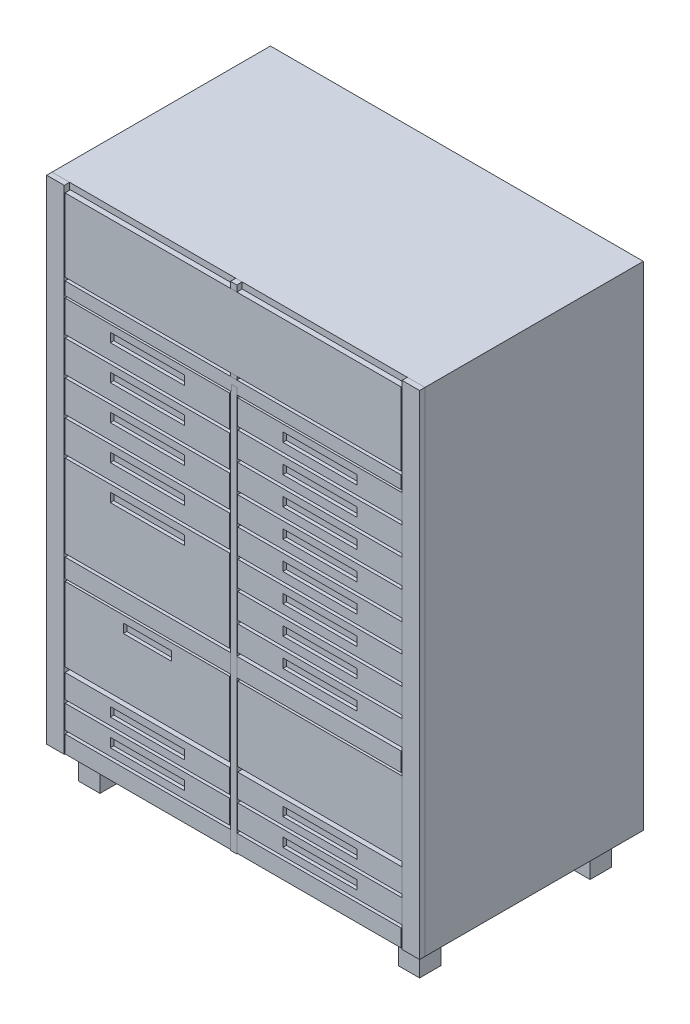
SolidWorks part; units mm, degrees
ref_plane "Front Plane" through (0, 0, 0) normal (0, 0, 1) x (1, 0, 0)
ref_plane "Top Plane" through (0, 0, 0) normal (0, 1, 0) x (1, 0, 0)
ref_plane "Right Plane" through (0, 0, 0) normal (1, 0, 0) x (0, 0, -1)
other "Configuration Table"
sketch "Sketch1" plane through (0, 0, 0) normal (0, 0, 1) x (1, 0, 0)
  line L1 (0, 120) -> (1400, 120)
  line L2 (0, 120) -> (0, 1970)
  line L3 (0, 1970) -> (1400, 1970)
  line L4 (1400, 120) -> (1400, 1970)
extrude "govde_kasa" add sketch "Sketch1" against normal blind 820 separate body
sketch "Sketch2" plane through (0, 0, 0) normal (0, 1, 0) x (1, 0, 0)
  line L1 (60, 40) -> (140, 40)
  line L2 (60, 40) -> (60, 120)
  line L3 (60, 120) -> (140, 120)
  line L4 (140, 40) -> (140, 120)
extrude "ayak_1" add sketch "Sketch2" along normal blind 120 separate body
sketch "Sketch3" plane through (0, 0, 0) normal (0, 1, 0) x (1, 0, 0)
  line L1 (1260, 40) -> (1340, 40)
  line L2 (1260, 40) -> (1260, 120)
  line L3 (1260, 120) -> (1340, 120)
  line L4 (1340, 40) -> (1340, 120)
extrude "ayak_2" add sketch "Sketch3" along normal blind 120 separate body
sketch "Sketch4" plane through (0, 0, 0) normal (0, 1, 0) x (1, 0, 0)
  line L1 (60, 680) -> (140, 680)
  line L2 (60, 680) -> (60, 760)
  line L3 (60, 760) -> (140, 760)
  line L4 (140, 680) -> (140, 760)
extrude "ayak_3" add sketch "Sketch4" along normal blind 120 separate body
sketch "Sketch5" plane through (0, 0, 0) normal (0, 1, 0) x (1, 0, 0)
  line L1 (1260, 680) -> (1340, 680)
  line L2 (1260, 680) -> (1260, 760)
  line L3 (1260, 760) -> (1340, 760)
  line L4 (1340, 680) -> (1340, 760)
extrude "ayak_4" add sketch "Sketch5" along normal blind 120 separate body
sketch "Sketch6" plane through (0, 0, 0) normal (0, 0, 1) x (1, 0, 0)
  line L1 (0, 120) -> (66, 120)
  line L2 (0, 120) -> (0, 1970)
  line L3 (0, 1970) -> (66, 1970)
  line L4 (66, 120) -> (66, 1970)
extrude "sove_sol" add sketch "Sketch6" along normal blind 20 separate body
sketch "Sketch7" plane through (0, 0, 0) normal (0, 0, 1) x (1, 0, 0)
  line L1 (690, 120) -> (714, 120)
  line L2 (690, 120) -> (690, 1970)
  line L3 (690, 1970) -> (714, 1970)
  line L4 (714, 120) -> (714, 1970)
extrude "sove_orta" add sketch "Sketch7" along normal blind 20 separate body
sketch "Sketch8" plane through (0, 0, 0) normal (0, 0, 1) x (1, 0, 0)
  line L1 (1334, 120) -> (1400, 120)
  line L2 (1334, 120) -> (1334, 1970)
  line L3 (1334, 1970) -> (1400, 1970)
  line L4 (1400, 120) -> (1400, 1970)
extrude "sove_sag" add sketch "Sketch8" along normal blind 20 separate body
sketch "Sketch9" plane through (0, 0, 0) normal (0, 0, 1) x (1, 0, 0)
  line L1 (69, 1673) -> (1331, 1673)
  line L2 (69, 1673) -> (69, 1947)
  line L3 (69, 1947) -> (1331, 1947)
  line L4 (1331, 1673) -> (1331, 1947)
extrude "panel_sogutma" add sketch "Sketch9" along normal blind 20 separate body
sketch "Sketch10" plane through (0, 0, 0) normal (0, 0, 1) x (1, 0, 0)
  line L1 (69, 1613) -> (1331, 1613)
  line L2 (69, 1613) -> (69, 1661)
  line L3 (69, 1661) -> (1331, 1661)
  line L4 (1331, 1613) -> (1331, 1661)
extrude "panel_bant_ust" add sketch "Sketch10" along normal blind 20 separate body
sketch "Sketch11" plane through (0, 0, 0) normal (0, 0, 1) x (1, 0, 0)
  line L1 (69, 1487) -> (687, 1487)
  line L2 (69, 1487) -> (69, 1605)
  line L3 (69, 1605) -> (687, 1605)
  line L4 (687, 1487) -> (687, 1605)
extrude "cekmece_icecek_1" add sketch "Sketch11" along normal blind 20 separate body
sketch "Sketch12" plane through (0, 0, 0) normal (0, 0, 1) x (1, 0, 0)
  line L1 (238.95, 1545) -> (517.05, 1545)
  line L2 (238.95, 1545) -> (238.95, 1579)
  line L3 (238.95, 1579) -> (517.05, 1579)
  line L4 (517.05, 1545) -> (517.05, 1579)
extrude "cekmece_icecek_1_kulp" cut sketch "Sketch12" along normal blind 13 from offset 7
sketch "Sketch13" plane through (0, 0, 0) normal (0, 0, 1) x (1, 0, 0)
  line L1 (69, 1357) -> (687, 1357)
  line L2 (69, 1357) -> (69, 1475)
  line L3 (69, 1475) -> (687, 1475)
  line L4 (687, 1357) -> (687, 1475)
extrude "cekmece_icecek_2" add sketch "Sketch13" along normal blind 20 separate body
sketch "Sketch14" plane through (0, 0, 0) normal (0, 0, 1) x (1, 0, 0)
  line L1 (238.95, 1415) -> (517.05, 1415)
  line L2 (238.95, 1415) -> (238.95, 1449)
  line L3 (238.95, 1449) -> (517.05, 1449)
  line L4 (517.05, 1415) -> (517.05, 1449)
extrude "cekmece_icecek_2_kulp" cut sketch "Sketch14" along normal blind 13 from offset 7
sketch "Sketch15" plane through (0, 0, 0) normal (0, 0, 1) x (1, 0, 0)
  line L1 (69, 1227) -> (687, 1227)
  line L2 (69, 1227) -> (69, 1345)
  line L3 (69, 1345) -> (687, 1345)
  line L4 (687, 1227) -> (687, 1345)
extrude "cekmece_icecek_3" add sketch "Sketch15" along normal blind 20 separate body
sketch "Sketch16" plane through (0, 0, 0) normal (0, 0, 1) x (1, 0, 0)
  line L1 (238.95, 1285) -> (517.05, 1285)
  line L2 (238.95, 1285) -> (238.95, 1319)
  line L3 (238.95, 1319) -> (517.05, 1319)
  line L4 (517.05, 1285) -> (517.05, 1319)
extrude "cekmece_icecek_3_kulp" cut sketch "Sketch16" along normal blind 13 from offset 7
sketch "Sketch17" plane through (0, 0, 0) normal (0, 0, 1) x (1, 0, 0)
  line L1 (69, 1097) -> (687, 1097)
  line L2 (69, 1097) -> (69, 1215)
  line L3 (69, 1215) -> (687, 1215)
  line L4 (687, 1097) -> (687, 1215)
extrude "cekmece_icecek_4" add sketch "Sketch17" along normal blind 20 separate body
sketch "Sketch18" plane through (0, 0, 0) normal (0, 0, 1) x (1, 0, 0)
  line L1 (238.95, 1155) -> (517.05, 1155)
  line L2 (238.95, 1155) -> (238.95, 1189)
  line L3 (238.95, 1189) -> (517.05, 1189)
  line L4 (517.05, 1155) -> (517.05, 1189)
extrude "cekmece_icecek_4_kulp" cut sketch "Sketch18" along normal blind 13 from offset 7
sketch "Sketch19" plane through (0, 0, 0) normal (0, 0, 1) x (1, 0, 0)
  line L1 (69, 775) -> (687, 775)
  line L2 (69, 775) -> (69, 1085)
  line L3 (69, 1085) -> (687, 1085)
  line L4 (687, 775) -> (687, 1085)
extrude "cekmece_1L" add sketch "Sketch19" along normal blind 20 separate body
sketch "Sketch20" plane through (0, 0, 0) normal (0, 0, 1) x (1, 0, 0)
  line L1 (238.95, 1025) -> (517.05, 1025)
  line L2 (238.95, 1025) -> (238.95, 1059)
  line L3 (238.95, 1059) -> (517.05, 1059)
  line L4 (517.05, 1025) -> (517.05, 1059)
extrude "cekmece_1L_kulp" cut sketch "Sketch20" along normal blind 13 from offset 7
sketch "Sketch21" plane through (0, 0, 0) normal (0, 0, 1) x (1, 0, 0)
  line L1 (717, 1512) -> (1335, 1512)
  line L2 (717, 1512) -> (717, 1605)
  line L3 (717, 1605) -> (1335, 1605)
  line L4 (1335, 1512) -> (1335, 1605)
extrude "cekmece_taze_1" add sketch "Sketch21" along normal blind 20 separate body
sketch "Sketch22" plane through (0, 0, 0) normal (0, 0, 1) x (1, 0, 0)
  line L1 (886.95, 1545) -> (1165.05, 1545)
  line L2 (886.95, 1545) -> (886.95, 1579)
  line L3 (886.95, 1579) -> (1165.05, 1579)
  line L4 (1165.05, 1545) -> (1165.05, 1579)
extrude "cekmece_taze_1_kulp" cut sketch "Sketch22" along normal blind 13 from offset 7
sketch "Sketch23" plane through (0, 0, 0) normal (0, 0, 1) x (1, 0, 0)
  line L1 (717, 1407) -> (1335, 1407)
  line L2 (717, 1407) -> (717, 1500)
  line L3 (717, 1500) -> (1335, 1500)
  line L4 (1335, 1407) -> (1335, 1500)
extrude "cekmece_taze_2" add sketch "Sketch23" along normal blind 20 separate body
sketch "Sketch24" plane through (0, 0, 0) normal (0, 0, 1) x (1, 0, 0)
  line L1 (886.95, 1440) -> (1165.05, 1440)
  line L2 (886.95, 1440) -> (886.95, 1474)
  line L3 (886.95, 1474) -> (1165.05, 1474)
  line L4 (1165.05, 1440) -> (1165.05, 1474)
extrude "cekmece_taze_2_kulp" cut sketch "Sketch24" along normal blind 13 from offset 7
sketch "Sketch25" plane through (0, 0, 0) normal (0, 0, 1) x (1, 0, 0)
  line L1 (717, 1302) -> (1335, 1302)
  line L2 (717, 1302) -> (717, 1395)
  line L3 (717, 1395) -> (1335, 1395)
  line L4 (1335, 1302) -> (1335, 1395)
extrude "cekmece_taze_3" add sketch "Sketch25" along normal blind 20 separate body
sketch "Sketch26" plane through (0, 0, 0) normal (0, 0, 1) x (1, 0, 0)
  line L1 (886.95, 1335) -> (1165.05, 1335)
  line L2 (886.95, 1335) -> (886.95, 1369)
  line L3 (886.95, 1369) -> (1165.05, 1369)
  line L4 (1165.05, 1335) -> (1165.05, 1369)
extrude "cekmece_taze_3_kulp" cut sketch "Sketch26" along normal blind 13 from offset 7
sketch "Sketch27" plane through (0, 0, 0) normal (0, 0, 1) x (1, 0, 0)
  line L1 (717, 1197) -> (1335, 1197)
  line L2 (717, 1197) -> (717, 1290)
  line L3 (717, 1290) -> (1335, 1290)
  line L4 (1335, 1197) -> (1335, 1290)
extrude "cekmece_taze_4" add sketch "Sketch27" along normal blind 20 separate body
sketch "Sketch28" plane through (0, 0, 0) normal (0, 0, 1) x (1, 0, 0)
  line L1 (886.95, 1230) -> (1165.05, 1230)
  line L2 (886.95, 1230) -> (886.95, 1264)
  line L3 (886.95, 1264) -> (1165.05, 1264)
  line L4 (1165.05, 1230) -> (1165.05, 1264)
extrude "cekmece_taze_4_kulp" cut sketch "Sketch28" along normal blind 13 from offset 7
sketch "Sketch29" plane through (0, 0, 0) normal (0, 0, 1) x (1, 0, 0)
  line L1 (717, 1092) -> (1335, 1092)
  line L2 (717, 1092) -> (717, 1185)
  line L3 (717, 1185) -> (1335, 1185)
  line L4 (1335, 1092) -> (1335, 1185)
extrude "cekmece_taze_5" add sketch "Sketch29" along normal blind 20 separate body
sketch "Sketch30" plane through (0, 0, 0) normal (0, 0, 1) x (1, 0, 0)
  line L1 (886.95, 1125) -> (1165.05, 1125)
  line L2 (886.95, 1125) -> (886.95, 1159)
  line L3 (886.95, 1159) -> (1165.05, 1159)
  line L4 (1165.05, 1125) -> (1165.05, 1159)
extrude "cekmece_taze_5_kulp" cut sketch "Sketch30" along normal blind 13 from offset 7
sketch "Sketch31" plane through (0, 0, 0) normal (0, 0, 1) x (1, 0, 0)
  line L1 (717, 987) -> (1335, 987)
  line L2 (717, 987) -> (717, 1080)
  line L3 (717, 1080) -> (1335, 1080)
  line L4 (1335, 987) -> (1335, 1080)
extrude "cekmece_taze_6" add sketch "Sketch31" along normal blind 20 separate body
sketch "Sketch32" plane through (0, 0, 0) normal (0, 0, 1) x (1, 0, 0)
  line L1 (886.95, 1020) -> (1165.05, 1020)
  line L2 (886.95, 1020) -> (886.95, 1054)
  line L3 (886.95, 1054) -> (1165.05, 1054)
  line L4 (1165.05, 1020) -> (1165.05, 1054)
extrude "cekmece_taze_6_kulp" cut sketch "Sketch32" along normal blind 13 from offset 7
sketch "Sketch33" plane through (0, 0, 0) normal (0, 0, 1) x (1, 0, 0)
  line L1 (717, 882) -> (1335, 882)
  line L2 (717, 882) -> (717, 975)
  line L3 (717, 975) -> (1335, 975)
  line L4 (1335, 882) -> (1335, 975)
extrude "cekmece_taze_7" add sketch "Sketch33" along normal blind 20 separate body
sketch "Sketch34" plane through (0, 0, 0) normal (0, 0, 1) x (1, 0, 0)
  line L1 (886.95, 915) -> (1165.05, 915)
  line L2 (886.95, 915) -> (886.95, 949)
  line L3 (886.95, 949) -> (1165.05, 949)
  line L4 (1165.05, 915) -> (1165.05, 949)
extrude "cekmece_taze_7_kulp" cut sketch "Sketch34" along normal blind 13 from offset 7
sketch "Sketch35" plane through (0, 0, 0) normal (0, 0, 1) x (1, 0, 0)
  line L1 (717, 777) -> (1335, 777)
  line L2 (717, 777) -> (717, 870)
  line L3 (717, 870) -> (1335, 870)
  line L4 (1335, 777) -> (1335, 870)
extrude "cekmece_taze_8" add sketch "Sketch35" along normal blind 20 separate body
sketch "Sketch36" plane through (0, 0, 0) normal (0, 0, 1) x (1, 0, 0)
  line L1 (886.95, 810) -> (1165.05, 810)
  line L2 (886.95, 810) -> (886.95, 844)
  line L3 (886.95, 844) -> (1165.05, 844)
  line L4 (1165.05, 810) -> (1165.05, 844)
extrude "cekmece_taze_8_kulp" cut sketch "Sketch36" along normal blind 13 from offset 7
sketch "Sketch37" plane through (0, 0, 0) normal (0, 0, 1) x (1, 0, 0)
  line L1 (69, 693) -> (1331, 693)
  line L2 (69, 693) -> (69, 763)
  line L3 (69, 763) -> (1331, 763)
  line L4 (1331, 693) -> (1331, 763)
extrude "panel_ayirici_PU80" add sketch "Sketch37" along normal blind 20 separate body
sketch "Sketch38" plane through (0, 0, 0) normal (0, 0, 1) x (1, 0, 0)
  line L1 (69, 406) -> (687, 406)
  line L2 (69, 406) -> (69, 684)
  line L3 (69, 684) -> (687, 684)
  line L4 (687, 406) -> (687, 684)
extrude "klape_kaset_kati" add sketch "Sketch38" along normal blind 20 separate body
sketch "Sketch39" plane through (0, 0, 0) normal (0, 0, 1) x (1, 0, 0)
  line L1 (288, 624) -> (468, 624)
  line L2 (288, 624) -> (288, 658)
  line L3 (288, 658) -> (468, 658)
  line L4 (468, 624) -> (468, 658)
extrude "klape_kaset_kati_kulp" cut sketch "Sketch39" along normal blind 13 from offset 7
sketch "Sketch40" plane through (0, 0, 0) normal (0, 0, 1) x (1, 0, 0)
  line L1 (717, 406) -> (1335, 406)
  line L2 (717, 406) -> (717, 684)
  line L3 (717, 684) -> (1335, 684)
  line L4 (1335, 406) -> (1335, 684)
extrude "panel_bos_bant" add sketch "Sketch40" along normal blind 20 separate body
sketch "Sketch41" plane through (0, 0, 0) normal (0, 0, 1) x (1, 0, 0)
  line L1 (69, 300) -> (687, 300)
  line L2 (69, 300) -> (69, 388)
  line L3 (69, 388) -> (687, 388)
  line L4 (687, 300) -> (687, 388)
extrude "cekmece_donmus_1" add sketch "Sketch41" along normal blind 20 separate body
sketch "Sketch42" plane through (0, 0, 0) normal (0, 0, 1) x (1, 0, 0)
  line L1 (238.95, 328) -> (517.05, 328)
  line L2 (238.95, 328) -> (238.95, 362)
  line L3 (238.95, 362) -> (517.05, 362)
  line L4 (517.05, 328) -> (517.05, 362)
extrude "cekmece_donmus_1_kulp" cut sketch "Sketch42" along normal blind 13 from offset 7
sketch "Sketch43" plane through (0, 0, 0) normal (0, 0, 1) x (1, 0, 0)
  line L1 (69, 200) -> (687, 200)
  line L2 (69, 200) -> (69, 288)
  line L3 (69, 288) -> (687, 288)
  line L4 (687, 200) -> (687, 288)
extrude "cekmece_donmus_2" add sketch "Sketch43" along normal blind 20 separate body
sketch "Sketch44" plane through (0, 0, 0) normal (0, 0, 1) x (1, 0, 0)
  line L1 (238.95, 228) -> (517.05, 228)
  line L2 (238.95, 228) -> (238.95, 262)
  line L3 (238.95, 262) -> (517.05, 262)
  line L4 (517.05, 228) -> (517.05, 262)
extrude "cekmece_donmus_2_kulp" cut sketch "Sketch44" along normal blind 13 from offset 7
sketch "Sketch45" plane through (0, 0, 0) normal (0, 0, 1) x (1, 0, 0)
  line L1 (717, 300) -> (1335, 300)
  line L2 (717, 300) -> (717, 388)
  line L3 (717, 388) -> (1335, 388)
  line L4 (1335, 300) -> (1335, 388)
extrude "cekmece_donmus_3" add sketch "Sketch45" along normal blind 20 separate body
sketch "Sketch46" plane through (0, 0, 0) normal (0, 0, 1) x (1, 0, 0)
  line L1 (886.95, 328) -> (1165.05, 328)
  line L2 (886.95, 328) -> (886.95, 362)
  line L3 (886.95, 362) -> (1165.05, 362)
  line L4 (1165.05, 328) -> (1165.05, 362)
extrude "cekmece_donmus_3_kulp" cut sketch "Sketch46" along normal blind 13 from offset 7
sketch "Sketch47" plane through (0, 0, 0) normal (0, 0, 1) x (1, 0, 0)
  line L1 (717, 200) -> (1335, 200)
  line L2 (717, 200) -> (717, 288)
  line L3 (717, 288) -> (1335, 288)
  line L4 (1335, 200) -> (1335, 288)
extrude "cekmece_donmus_4" add sketch "Sketch47" along normal blind 20 separate body
sketch "Sketch48" plane through (0, 0, 0) normal (0, 0, 1) x (1, 0, 0)
  line L1 (886.95, 228) -> (1165.05, 228)
  line L2 (886.95, 228) -> (886.95, 262)
  line L3 (886.95, 262) -> (1165.05, 262)
  line L4 (1165.05, 228) -> (1165.05, 262)
extrude "cekmece_donmus_4_kulp" cut sketch "Sketch48" along normal blind 13 from offset 7
sketch "Sketch49" plane through (0, 0, 0) normal (0, 0, 1) x (1, 0, 0)
  line L1 (69, 123) -> (1331, 123)
  line L2 (69, 123) -> (69, 188)
  line L3 (69, 188) -> (1331, 188)
  line L4 (1331, 123) -> (1331, 188)
extrude "panel_bant_alt" add sketch "Sketch49" along normal blind 20 separate body
